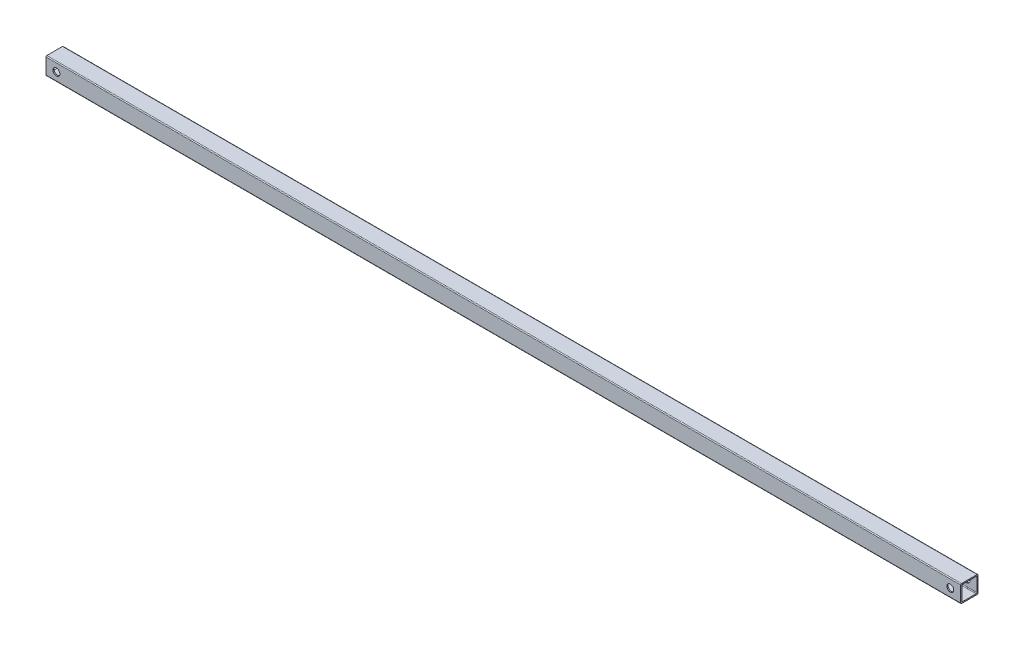
SolidWorks part; units mm, degrees
ref_plane "Front" through (0, 0, 0) normal (0, 0, 1) x (1, 0, 0)
ref_plane "Top" through (0, 0, 0) normal (0, 1, 0) x (1, 0, 0)
ref_plane "Right" through (0, 0, 0) normal (1, 0, 0) x (0, 0, -1)
sketch "Sketch1" plane through (0, 0, 0) normal (1, 0, 0) x (0, 0, -1)
  line L0 (-13.7668, 0) -> (-15.875, 0) construction
  line L1 (14.2875, -15.875) -> (-14.2875, -15.875) construction
  line L2 (15.875, -14.2875) -> (15.875, 14.2875) construction
  line L3 (14.2875, 15.875) -> (-14.2875, 15.875) construction
  line L4 (-15.875, -14.2875) -> (-15.875, 14.2875) construction
  line L5 (15.875, -15.875) -> (-15.875, 15.875) construction
  line L6 (15.875, 15.875) -> (-15.875, -15.875) construction
  line L7 (12.3901, 13.7668) -> (-12.3901, 13.7668) construction
  line L8 (13.7668, 12.3901) -> (13.7668, -12.3901) construction
  line L9 (12.3901, -13.7668) -> (-12.3901, -13.7668) construction
  line L10 (-13.7668, 12.3901) -> (-13.7668, -12.3901) construction
  line L11 (13.7668, 13.7668) -> (-13.7668, -13.7668) construction
  line L12 (13.7668, -13.7668) -> (-13.7668, 13.7668) construction
  line L13 (0, -13.7668) -> (0, -15.875) construction
  line L14 (13.7668, -12.3901) -> (13.7668, -15.875) construction
  line L15 (13.7668, 0) -> (15.875, 0) construction
  line L16 (13.7668, -15.875) -> (15.875, -15.875) construction
  arc A0 (-12.3901, -13.7668) -> (-13.7668, -12.3901) centre (-12.3901, -12.3901) cw construction
  arc A1 (13.7668, -12.3901) -> (12.3901, -13.7668) centre (12.3901, -12.3901) cw construction
  arc A2 (12.3901, 13.7668) -> (13.7668, 12.3901) centre (12.3901, 12.3901) cw construction
  arc A3 (-12.3901, 13.7668) -> (-13.7668, 12.3901) centre (-12.3901, 12.3901) ccw construction
  arc A4 (14.2875, -15.875) -> (15.875, -14.2875) centre (14.2875, -14.2875) ccw construction
  arc A5 (15.875, 14.2875) -> (14.2875, 15.875) centre (14.2875, 14.2875) ccw construction
  arc A6 (-14.2875, 15.875) -> (-15.875, 14.2875) centre (-14.2875, 14.2875) ccw construction
  arc A7 (-14.2875, -15.875) -> (-15.875, -14.2875) centre (-14.2875, -14.2875) cw construction
  point P0 (0, 0)
  point P6 (0, 0)
  dimension "D2" = 1.3767
  dimension "D3" = 1.5875
  dimension "Outside Width" = 31.75
  dimension "Ouside Height" = 31.75
  dimension "Inside Height" = 27.5336
  dimension "Wall Thickness" = 2.1082
sketch "Sketch2" plane through (0, 0, 0) normal (0, 0, 1) x (1, 0, 0)
  line L0 (-838.2, 0) -> (838.2, 0) construction
  point P3 (-808.5582, 0)
  point P4 (808.5582, 0)
  dimension "Length" = 1676.4
  dimension "D1" = 29.6418
  dimension "D2" = 29.6418
sketch "Sketch4" plane through (0, 0, 0) normal (1, 0, 0) x (0, 0, -1)
  line L8 (15.875, -14.2875) -> (15.875, 14.2875)
  line L9 (14.2875, 15.875) -> (-14.2875, 15.875)
  line L10 (-15.875, -14.2875) -> (-15.875, 14.2875)
  line L11 (14.2875, -15.875) -> (-14.2875, -15.875)
  line L12 (13.7668, 12.3901) -> (13.7668, -12.3901)
  line L13 (12.3901, -13.7668) -> (-12.3901, -13.7668)
  line L14 (-13.7668, 12.3901) -> (-13.7668, -12.3901)
  line L15 (12.3901, 13.7668) -> (-12.3901, 13.7668)
  arc A8 (15.875, 14.2875) -> (14.2875, 15.875) centre (14.2875, 14.2875) ccw
  arc A9 (-14.2875, 15.875) -> (-15.875, 14.2875) centre (-14.2875, 14.2875) ccw
  arc A10 (-15.875, -14.2875) -> (-14.2875, -15.875) centre (-14.2875, -14.2875) ccw
  arc A11 (14.2875, -15.875) -> (15.875, -14.2875) centre (14.2875, -14.2875) ccw
  arc A12 (12.3901, -13.7668) -> (13.7668, -12.3901) centre (12.3901, -12.3901) ccw
  arc A13 (-13.7668, -12.3901) -> (-12.3901, -13.7668) centre (-12.3901, -12.3901) ccw
  arc A14 (-12.3901, 13.7668) -> (-13.7668, 12.3901) centre (-12.3901, 12.3901) ccw
  arc A15 (13.7668, 12.3901) -> (12.3901, 13.7668) centre (12.3901, 12.3901) ccw
extrude "Boss-Extrude1" add sketch "Sketch4" along normal up to vertex (838.2 mm away) and the other way up to vertex (838.2 mm away)
sketch "Sketch5" plane through (0, 0, 15.875) normal (0, 0, 1) x (1, 0, 0)
  line L0 (838.2, 15.875) -> (-838.2, 15.875) construction
  line L1 (838.2, 14.2875) -> (838.2, -14.2875) construction
  line L2 (-838.2, 14.2875) -> (-838.2, -14.2875) construction
  line L3 (838.2, -15.875) -> (-838.2, -15.875) construction
  circle A0 centre (819.15, 0) radius 6.35
  circle A1 centre (-819.15, 0) radius 6.35
  dimension "D1" = 12.7
  dimension "D3" = 19.05
  dimension "D4" = 12.7
  dimension "D5" = 19.05
  dimension "D6" = 15.875
  dimension "D2" = 15.875
extrude "Cut-Extrude1" cut sketch "Sketch5" against normal through all
equation "\"D3@Sketch1\"=\"Outside Width@Sketch1\"*.05"
equation "\"D2@Sketch1\" = \"Inside Height@Sketch1\" * .05"
equation "\"D1@Sketch2\"=\"Outside Width@Sketch1\"-\"Wall Thickness@Sketch1\""
equation "\"D2@Sketch2\"=\"D1@Sketch2\""
